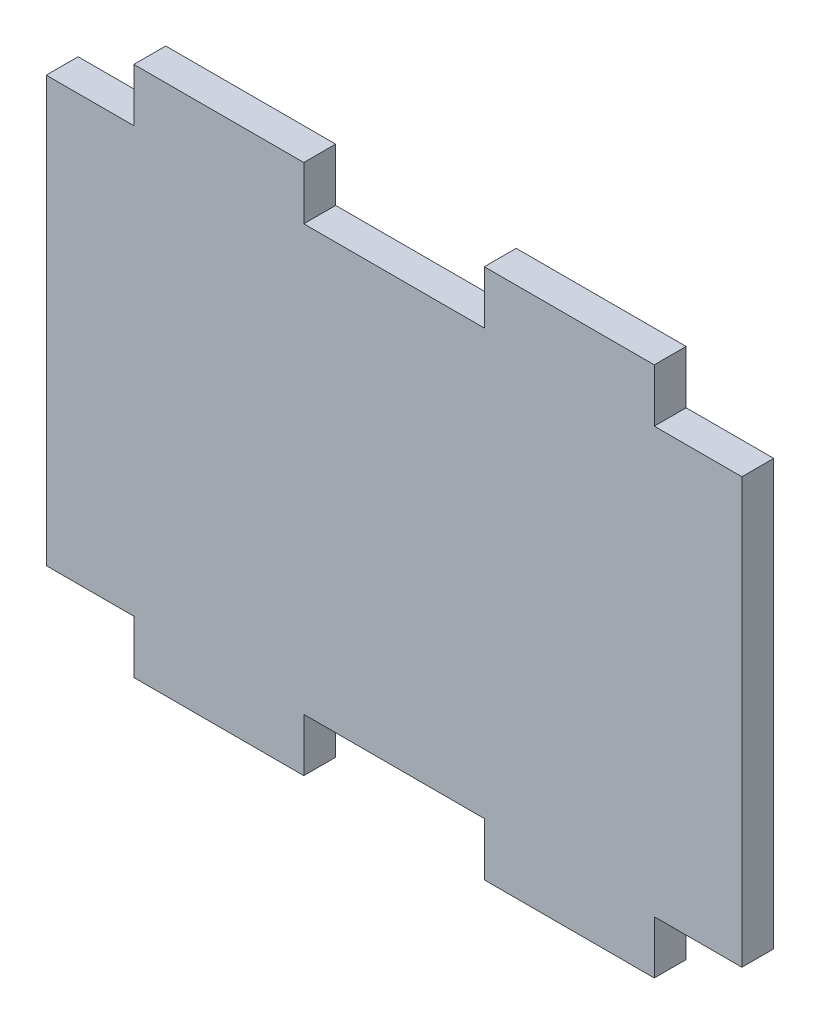
SolidWorks part; units mm, degrees
material "Hêtre"
ref_plane "Plan de face" through (0, 0, 0) normal (0, 0, 1) x (1, 0, 0)
ref_plane "Plan de dessus" through (0, 0, 0) normal (0, 1, 0) x (1, 0, 0)
ref_plane "Plan de droite" through (0, 0, 0) normal (1, 0, 0) x (0, 0, -1)
sketch "Esquisse1" plane through (0, 0, 0) normal (0, 0, 1) x (1, 0, 0)
  line L0 (49, -4) -> (49, 6)
  line L1 (49, 6) -> (65.5, 6)
  line L2 (49, -4) -> (17, -4)
  line L3 (17, -4) -> (17, 6)
  line L4 (17, 6) -> (-17, 6)
  line L5 (17, 6) -> (-17, 6) construction
  line L6 (-69.5, 46) -> (89.9125, 46) construction
  line L7 (-69.5, 86) -> (-69.5, 6) construction
  line L8 (65.5, 6) -> (65.5, 86)
  line L9 (17, 86) -> (-17, 86)
  line L10 (17, 96) -> (17, 86)
  line L11 (49, 96) -> (17, 96)
  line L12 (49, 86) -> (65.5, 86)
  line L13 (49, 96) -> (49, 86)
  line L14 (0, 107.7811) -> (0, -30.6309) construction
  line L15 (-49, 96) -> (-49, 86)
  line L16 (-49, 86) -> (-65.5, 86)
  line L17 (-49, 96) -> (-17, 96)
  line L18 (-17, 96) -> (-17, 86)
  line L19 (-65.5, 6) -> (-65.5, 86)
  line L20 (-17, -4) -> (-17, 6)
  line L21 (-49, -4) -> (-17, -4)
  line L22 (-49, 6) -> (-65.5, 6)
  line L23 (-49, -4) -> (-49, 6)
  point P20 (65.5, 46)
  point P34 (0, 86)
  point P36 (0, 6)
  point P39 (-65.5, 46)
  dimension "D1" = 10
  dimension "D2" = 65.5
extrude "Boss.-Extru.1" add sketch "Esquisse1" along normal blind 6 contours L19 L16 L15 L17 L18 L9 L10 L11 L13 L12 L8 L1 L0 L2 L3 L4 L20 L21 L23 L22
